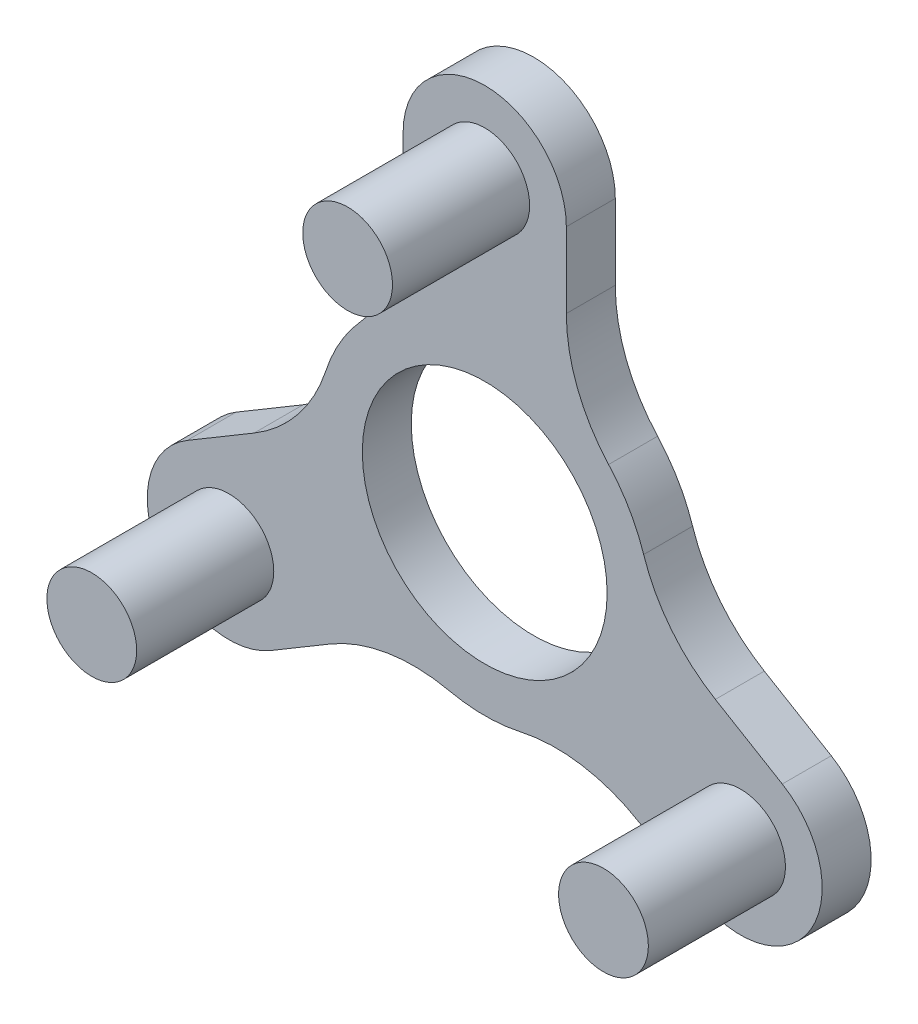
SolidWorks part; units mm, degrees
ref_plane "Alzado" through (0, 0, 0) normal (0, 0, 1) x (1, 0, 0)
ref_plane "Planta" through (0, 0, 0) normal (0, 1, 0) x (1, 0, 0)
ref_plane "Vista lateral" through (0, 0, 0) normal (1, 0, 0) x (0, 0, -1)
sketch "Croquis1" plane through (0, 0, 0) normal (0, 0, 1) x (1, 0, 0)
  line L0 (-18.2318, -4.7531) -> (-10.2435, 0)
  line L1 (-13.1183, -13.3469) -> (-5.359, -8.7299)
  line L2 (13.1183, -13.3469) -> (5.359, -8.7299)
  line L3 (-13.1183, -13.3469) -> (-18.2318, -4.7531)
  line L7 (13.1183, -13.3469) -> (18.2318, -4.7531)
  line L11 (-5, 18.2) -> (5, 18.2)
  line L15 (18.2318, -4.7531) -> (10.2435, 0)
  line L16 (-5, 18.2) -> (-5, 8.9404)
  line L17 (5, 18.2) -> (5, 8.9404)
  circle A0 centre (0, 18.2) radius 5
  circle A1 centre (15.6751, -9.05) radius 5
  circle A2 centre (-15.6751, -9.05) radius 5
  circle A3 centre (0, 0) radius 10.2435
  dimension "D7" = 10
  dimension "D8" = 10
  dimension "D9" = 10
  dimension "D1" = 90
  dimension "D2" = 90
  dimension "D3" = 90
  dimension "D4" = 18.1
  dimension "D5" = 18.1
  dimension "D6" = 18.2
  dimension "D10" = 90
  dimension "D11" = 90
  dimension "D12" = 90
extrude "Saliente-Extruir1" add sketch "Croquis1" along normal blind 3 contours L3 A2 | L3 A2 | A3 L0 A2 L1 | A3 | A3 L2 A1 L15 | A3 L17 A0 L16 | L11 A0 | L11 A0
sketch "Croquis2" plane through (0, 0, 3) normal (0, 0, 1) x (1, 0, 0)
  circle A0 centre (0, 18.2) radius 2.75
  circle A1 centre (15.6751, -9.05) radius 2.75
  circle A2 centre (-15.6751, -9.05) radius 2.75
  dimension "D1" = 5.5
  dimension "D2" = 5.5
  dimension "D3" = 5.5
sketch "Croquis3" plane through (0, 0, 3) normal (0, 0, 1) x (1, 0, 0)
  circle A0 centre (0, 0) radius 7.5
  dimension "D1" = 15
extrude "Cortar-Extruir2" cut sketch "Croquis3" against normal blind 10
fillet "Redondeo1" radius 10 6 edges at (-5.359, -8.7299, 1.5) (5.359, -8.7299, 1.5) (10.2435, 0, 1.5) (5, 8.9404, 1.5) (-5, 8.9404, 1.5) (-10.2435, 0, 1.5)
extrude "Saliente-Extruir2" add sketch "Croquis2" along normal blind 8.4
